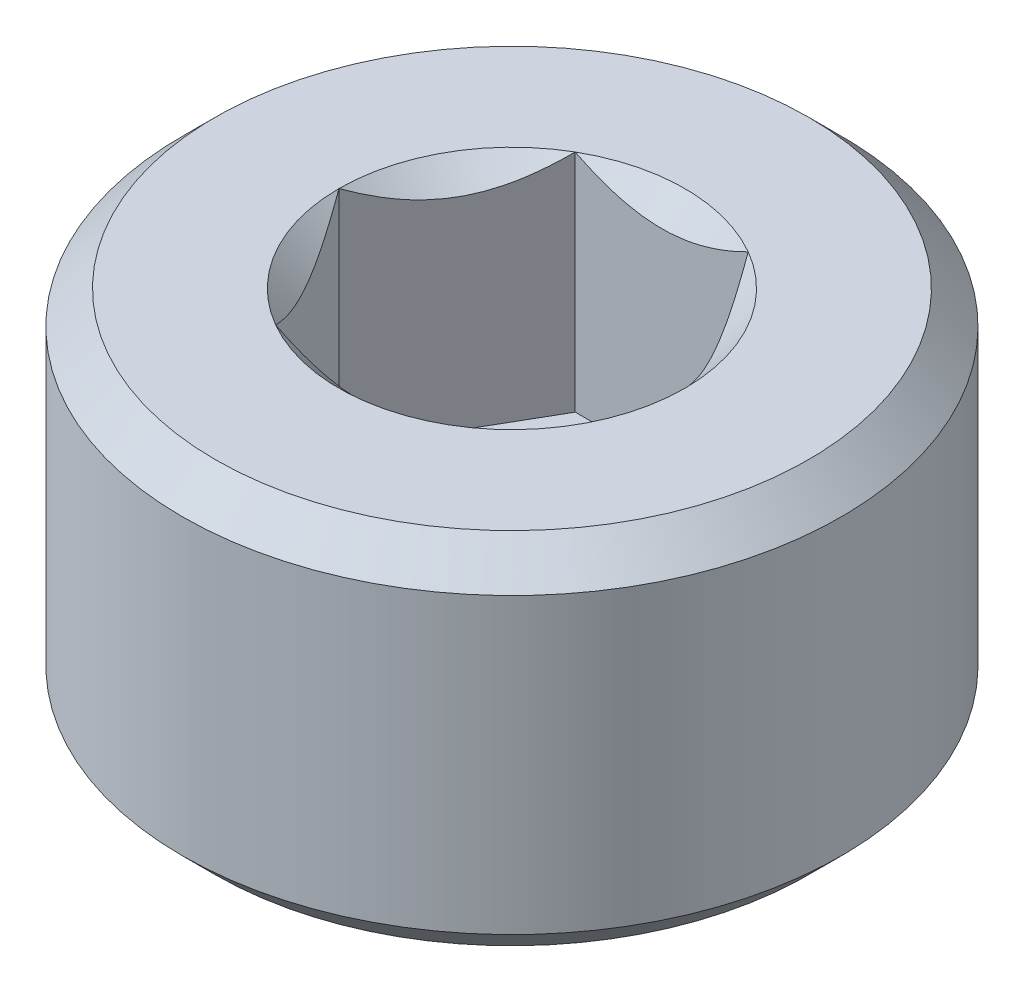
SolidWorks part; units mm, degrees
ref_plane "Front" through (0, 0, 0) normal (0, 0, 1) x (1, 0, 0)
ref_plane "Top" through (0, 0, 0) normal (0, 1, 0) x (1, 0, 0)
ref_plane "Right" through (0, 0, 0) normal (1, 0, 0) x (0, 0, -1)
sketch "Sketch1" plane through (0, 0, 0) normal (0, 1, 0) x (1, 0, 0)
  circle A0 centre (0, 0) radius 2.75
  dimension "D1" = 5.5
extrude "Boss-Extrude1" add sketch "Sketch1" along normal blind 3
sketch "Sketch2" plane through (0, 3, 0) normal (0, 1, 0) x (1, 0, 0)
  line L1 (0.7217, 1.25) -> (-0.7217, 1.25)
  line L2 (-0.7217, 1.25) -> (-1.4434, 0)
  line L3 (-1.4434, 0) -> (-0.7217, -1.25)
  line L4 (-0.7217, -1.25) -> (0.7217, -1.25)
  line L5 (0.7217, -1.25) -> (1.4434, 0)
  line L6 (1.4434, 0) -> (0.7217, 1.25)
  circle A0 centre (0, 0) radius 1.25 construction
  point P1 (0, 0)
  point P10 (0, 1.25)
  dimension "D1" = 2.5
extrude "Cut-Extrude1" cut sketch "Sketch2" against normal blind 1.88
sketch "Sketch5" plane through (0, 3, 0) normal (0, 1, 0) x (1, 0, 0)
  circle A0 centre (0, 0) radius 1.4434
extrude "Cut-Extrude2" cut sketch "Sketch5" against normal through all draft 45
chamfer "Chamfer1" distance 0.275 angle 45 2 edges at (0, 0, 2.75) (0, 3, 2.75)
